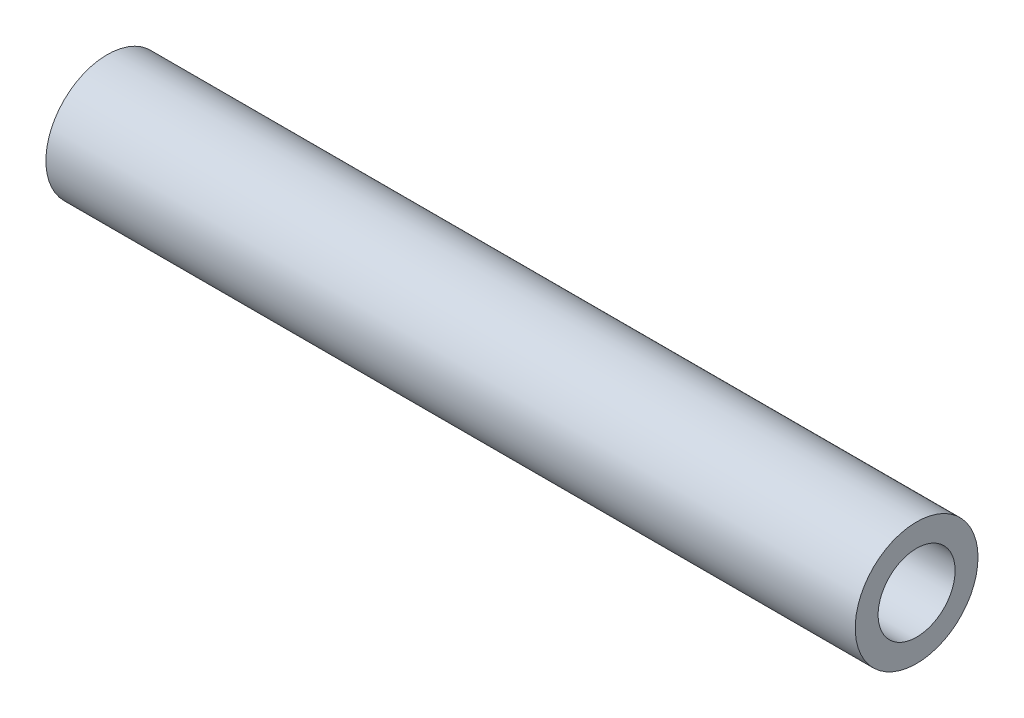
SolidWorks part; units mm, degrees
ref_plane "Front Plane" through (0, 0, 0) normal (0, 0, 1) x (1, 0, 0)
ref_plane "Top Plane" through (0, 0, 0) normal (0, 1, 0) x (1, 0, 0)
ref_plane "Right Plane" through (0, 0, 0) normal (1, 0, 0) x (0, 0, -1)
sketch "Sketch1" plane through (0, 0, 0) normal (1, 0, 0) x (0, 0, -1)
  circle A0 centre (0, 0) radius 3.9688
  circle A1 centre (0, 0) radius 2.4892
  dimension "D1" = 7.9375
  dimension "D2" = 4.9784
extrude "Boss-Extrude1" add sketch "Sketch1" along normal blind 52.324
